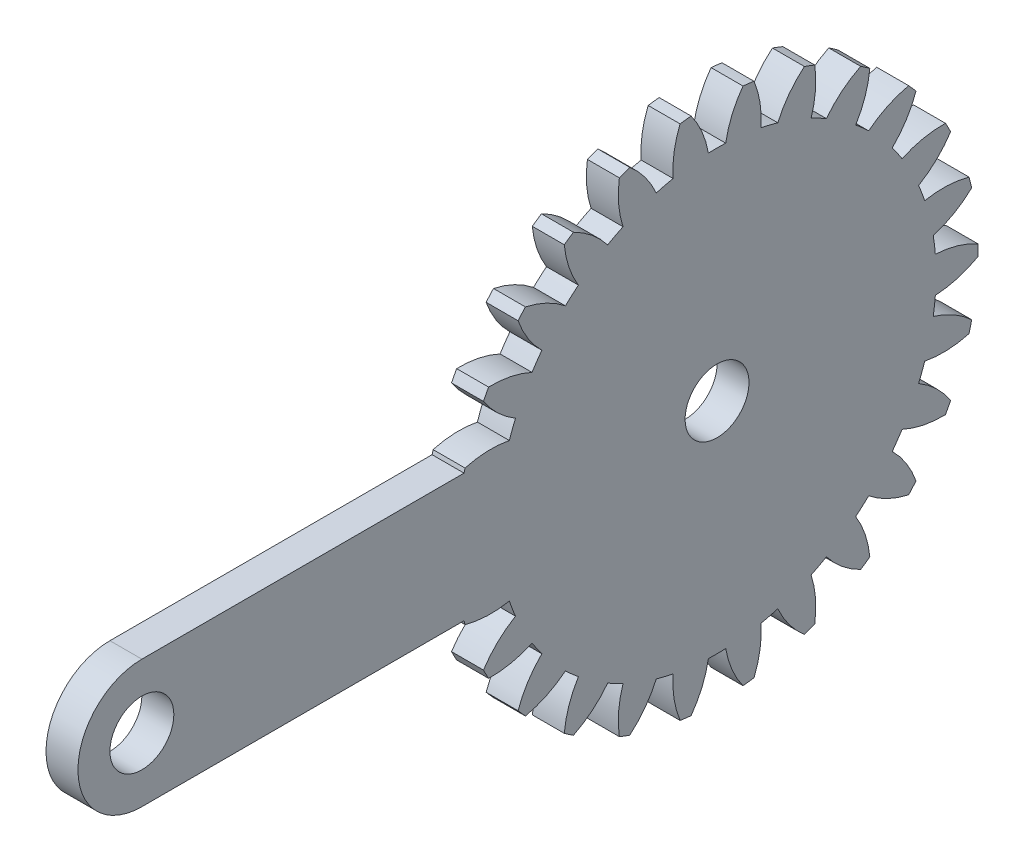
SolidWorks part; units mm, degrees
ref_plane "Plane1" through (0, 0, 0) normal (0, 0, 1) x (1, 0, 0)
ref_plane "Plane2" through (0, 0, 0) normal (0, 1, 0) x (1, 0, 0)
ref_plane "Plane3" through (0, 0, 0) normal (1, 0, 0) x (0, 0, -1)
sketch "HoldingSke" plane through (0, 0, 0) normal (0, 1, 0) x (1, 0, 0)
  line L0 (0, 0) -> (0.5136, -0.2505)
  line L1 (-15, 0) -> (100, 0) construction
  line L2 (0, 0) -> (-2.1039, 2.3779)
  line L3 (0, 0) -> (-11.863, 4.5341)
  line L4 (0, 0) -> (7.762, 3.7858)
  line L5 (0, 0) -> (-46.8476, -17.4728)
  line L6 (0, 0) -> (-2.4869, -1.6779)
  line L7 (-2.1039, 2.3779) -> (8.6586, 51.2059)
  line L8 (-76.2, 54.61) -> (-75.2, 54.61)
  line L9 (-71.009, 38.7566) -> (-53.1078, 45.2721)
  line L10 (-76.2, 71.12) -> (104.1128, 71.12)
  line L11 (0, 0) -> (-3, 0)
  line L12 (-76.2, 101.6) -> (-76.147, 101.6)
  line L13 (24.9733, 27.94) -> (52.9518, 28.4284)
  line L14 (24.9733, 27.94) -> (24.9743, 27.94)
  line L15 (24.9733, 27.94) -> (100.4006, 29.5858)
  line L16 (-63.627, -1.75) -> (-12.827, -1.75)
  circle A0 centre (0, 0) radius 3
  circle A1 centre (0, 0) radius 20.5615
  circle A2 centre (0, 0) radius 37.5
  circle A3 centre (0, 0) radius 3
  dimension "MHD" = 41.123
  dimension "Hub_dia" = 75
  dimension "Bore" = 6
  dimension "MBD" = 6
  dimension "Num_teeth" = 26
  dimension "Pitch" = 0.5714
  dimension "Overall_len" = 50
  dimension "Show_teeth" = 26
  dimension "Thickness" = 3
  dimension "OAL" = 50.0001
  dimension "T_dim" = 1
  dimension "Ap" = 20
  dimension "H" = 19.05
  dimension "Pitch_radius" = 180.3128
  dimension "Width" = 3
  dimension "Backlash" = 0.053
  dimension "Addendum_fac" = 1
  dimension "Dedendum_fac" = 1.25
  dimension "Clearance_fac" = 0.25
  dimension "Dedendum_add" = 0.001
  dimension "Module" = 1.75
sketch "BasProSke" plane through (0, 0, 0) normal (0, 1, 0) x (1, 0, 0)
  line L0 (-10, 0) -> (60, 0) construction
  line L1 (0, 0) -> (0, 24.5)
  line L2 (0, 0) -> (3, 0)
  line L3 (3, 0) -> (3, 24.5)
  line L4 (3, 24.5) -> (0, 24.5)
  dimension "Thickness" = 3
  dimension "Diameter" = 49
revolve "Base-Revolve" add sketch "BasProSke" angle 360 about L0
sketch "TooCutSke" plane through (0, 0, 0) normal (1, 0, 0) x (0, 0, -1)
  line L1 (0, 0) -> (0, 107) construction
  line L2 (0, 0) -> (-1.4663, 22.7027) construction
  line L3 (0, 0) -> (-5.4757, 45.0966) construction
  line L4 (-1.4663, 22.7027) -> (-2.7379, 22.5483) construction
  arc A0 (0.8134, 20.5454) -> (-0.8134, 20.5454) centre (0, 0) ccw
  arc A1 (2.4537, 24.4024) -> (-2.4537, 24.4024) centre (0, 0) ccw
  circle A2 centre (0, 0) radius 22.75 construction
  circle A3 centre (0, 0) radius 21.378 construction
  arc A4 (-0.8134, 20.5454) -> (-2.4537, 24.4024) centre (-9.7827, 19.0084) ccw
  arc A5 (2.4537, 24.4024) -> (0.8134, 20.5454) centre (9.7827, 19.0084) ccw
  dimension "Root_dia" = 41.123
  dimension "Overcut_dia" = 49.0508
  dimension "Pitch_dia" = 45.5
  dimension "Base_dia" = 42.756
  dimension "Flank_rad" = 9.1
  dimension "Half_ang" = 6.923
  dimension "Half_CT" = 1.2809
extrude "ToothCut" cut sketch "TooCutSke" along normal through all
fillet "Breaks" [suppressed] radius 0.035
fillet "RootFillets" [suppressed] radius 0.4385
pattern_circular "TeethCuts" count 26 every 13.846 about axis through (-10, 0, 0) along (1, 0, 0) of "ToothCut", "RootFillets", "Breaks"
sketch "HubNeaOneSke" plane through (0, 0, 0) normal (-1, 0, 0) x (0, 0, 1)
  circle A0 centre (0, 0) radius 20.5615
  dimension "Diameter" = 41.123
extrude "HubNearOne" [suppressed] add sketch "HubNeaOneSke" along normal blind 47.0001
sketch "HubNeaBotSke" plane through (0, 0, 0) normal (-1, 0, 0) x (0, 0, 1)
  circle A0 centre (0, 0) radius 20.5615
  dimension "Diameter" = 41.123
extrude "HubNearBoth" [suppressed] add sketch "HubNeaBotSke" along normal blind 23.5
ref_plane "FarPln" through (3, 0, 0) normal (1, 0, 0) x (0, 0, -1)
sketch "HubFarSke" plane through (3, 0, 0) normal (1, 0, 0) x (0, 0, -1)
  circle A0 centre (0, 0) radius 20.5615
  dimension "Diameter" = 41.123
extrude "HubFar" [suppressed] add sketch "HubFarSke" along normal blind 23.5
sketch "BorSke" plane through (0, 0, 0) normal (1, 0, 0) x (0, 0, -1)
  circle A0 centre (0, 0) radius 3
  dimension "Diameter" = 6
extrude "Bore" cut sketch "BorSke" along normal mid plane 100.0001
sketch "KeySke" plane through (0, 0, 0) normal (1, 0, 0) x (0, 0, -1)
  line L0 (-1, 0) -> (-1, 4)
  line L1 (-1, 4) -> (1, 4)
  line L2 (1, 4) -> (1, 0)
  line L3 (0, 0) -> (0, 34) construction
  line L4 (-1, 0) -> (1, 0)
  dimension "Offset" = 4
  dimension "Width" = 2
extrude "Keyway" [suppressed] cut sketch "KeySke" along normal mid plane 100.0001
pattern_circular "Keyway2" [suppressed] count 2 every 90 about axis through (-10, 0, 0) along (1, 0, 0)
sketch "Sketch2" plane through (0, 0, 0) normal (1, 0, 0) x (0, 0, -1)
  line L0 (0, 0) -> (-54, 0) construction
  line L1 (0, -6) -> (-54, -6)
  line L2 (0, 6) -> (-54, 6)
  arc A0 (0, -6) -> (0, 6) centre (0, 0) ccw
  arc A1 (-54, 6) -> (-54, -6) centre (-54, 0) ccw
  circle A2 centre (-54, 0) radius 3
  circle A3 centre (0, 0) radius 3
  point P3 (-27, 0)
  dimension "D1" = 54
  dimension "D2" = 12
extrude "Boss-Extrude1" add sketch "Sketch2" along normal blind 3
equation "' \"Module@HoldingSke\" = 6.35"
equation "' \"Num_teeth@HoldingSke\" = 12"
equation "' \"Ap@HoldingSke\" =  20"
equation "' \"Ap@HoldingSke\" = 20"
equation "' \"Width@HoldingSke\" = 0.5 * 25.4"
equation "' \"Hub_dia@HoldingSke\"= 1 * 25.4"
equation "' \"Hub_dia@HoldingSke\" = 1 * 25.4"
equation "' \"Overall_len@HoldingSke\" = 1.0 * 25.4"
equation "' \"Bore@HoldingSke\" = 0.75 * 25.4"
equation "' \"T_dim@HoldingSke\" = 0.1 * 25.4"
equation "' \"Width@KeySke\" = 0.25 * 25.4"
equation "' \"Show_teeth@HoldingSke\" = 13"
equation "' \"Backlash@HoldingSke\" = 0.009 * 25.4"
equation "' \"Addendum_fac@HoldingSke\" = 1.0"
equation "' \"Dedendum_fac@HoldingSke\" = 1.25"
equation "' \"Dedendum_add@HoldingSke\" = 0.00005 * 25.4"
equation "' \"Clearance_fac@HoldingSke\" = 0.25"
equation "\"Pitch@HoldingSke\" = 1 / \"Module@HoldingSke\""
equation "\"Overcut_dia@TooCutSke\" = (\"Num_teeth@HoldingSke\" + 2 * \"Addendum_fac@HoldingSke\") / \"Pitch@HoldingSke\" + 0.002 * 25.4"
equation "\"Pitch_dia@TooCutSke\" = \"Num_teeth@HoldingSke\" / \"Pitch@HoldingSke\""
equation "\"Base_dia@TooCutSke\" = \"Num_teeth@HoldingSke\" / \"Pitch@HoldingSke\" * cos((\"Ap@HoldingSke\"  * 3.14159265 / 180))"
equation "\"Root_dia@TooCutSke\" = (\"Num_teeth@HoldingSke\" + 2) / \"Pitch@HoldingSke\" - 2 * (\"Addendum_fac@HoldingSke\" + \"Dedendum_fac@HoldingSke\") / \"Pitch@HoldingSke\" - \"Dedendum_add@HoldingSke\" * 2"
equation "\"Half_ang@TooCutSke\" = 180 / \"Num_teeth@HoldingSke\""
equation "\"Half_CT@TooCutSke\" = \"Num_teeth@HoldingSke\" / \"Pitch@HoldingSke\" * sin((3.14159265 / 2 / \"Num_teeth@HoldingSke\")) / 2 - 7 * \"Backlash@HoldingSke\" / 4"
equation "\"Flank_rad@TooCutSke\" = \"Num_teeth@HoldingSke\" / \"Pitch@HoldingSke\" / 5"
equation "\"Radius@RootFillets\" = \"Clearance_fac@HoldingSke\" / \"Pitch@HoldingSke\" + \"Dedendum_add@HoldingSke\""
equation "\"Break_rad@Breaks\" = 0.02 / \"Pitch@HoldingSke\""
equation "\"Thickness@HoldingSke\" = \"Width@HoldingSke\""
equation "\"OAL@HoldingSke\" = \"Thickness@HoldingSke\""
equation "\"MHD@HoldingSke\" = (\"Num_teeth@HoldingSke\" + 2) / \"Pitch@HoldingSke\" - 2 * (\"Addendum_fac@HoldingSke\" + \"Dedendum_fac@HoldingSke\")  / \"Pitch@HoldingSke\" - \"Dedendum_add@HoldingSke\" * 2"
equation "\"MBD@HoldingSke\" = (\"Num_teeth@HoldingSke\" + 2) / \"Pitch@HoldingSke\" - 2 * (\"Addendum_fac@HoldingSke\" + \"Dedendum_fac@HoldingSke\")  / \"Pitch@HoldingSke\" - \"Dedendum_add@HoldingSke\" * 2 - 0.002 * 25.4"
equation "\"MHD@HoldingSke\" = ((sgn( \"MHD@HoldingSke\" - \"Hub_dia@HoldingSke\" )-1)*( \"MHD@HoldingSke\" - \"Hub_dia@HoldingSke\" ))/-2+ \"Hub_dia@HoldingSke\""
equation "\"MBD@HoldingSke\" = ((sgn( \"MBD@HoldingSke\" - \"Bore@HoldingSke\" )-1)*( \"MBD@HoldingSke\" - \"Bore@HoldingSke\" ))/-2+ \"Bore@HoldingSke\""
equation "\"OAL@HoldingSke\" = ((sgn( \"OAL@HoldingSke\" - \"Overall_len@HoldingSke\" )+1)*( \"OAL@HoldingSke\" - \"Overall_len@HoldingSke\" ))/2 + \"Overall_len@HoldingSke\" + 0.000002 * 25.4"
equation "\"Num_teeth@TeethCuts\" = int( \"Show_teeth@HoldingSke\" ) + 1"
equation "\"Num_teeth@TeethCuts\" = ((sgn( \"Num_teeth@TeethCuts\" - \"Num_teeth@HoldingSke\" )-1)*( \"Num_teeth@TeethCuts\" - \"Num_teeth@HoldingSke\" ))/-2+ \"Num_teeth@HoldingSke\""
equation "\"Num_teeth@TeethCuts\" = ((sgn( \"Num_teeth@TeethCuts\" - 2.0)+1)*( \"Num_teeth@TeethCuts\" - 2.0))/2 +2.0"
equation "\"Angle@TeethCuts\" = 360.0 / \"Num_teeth@HoldingSke\""
equation "\"Diameter@BasProSke\" = (\"Num_teeth@HoldingSke\" + 2 * \"Addendum_fac@HoldingSke\") / \"Pitch@HoldingSke\""
equation "\"Thickness@BasProSke\"  = \"Thickness@HoldingSke\""
equation "' \"Fillet_rad@BasProSke\" =  \"Thickness@HoldingSke\" * 0.05"
equation "' \"Fillet_rad@BasProSke\" = \"Thickness@HoldingSke\" * 0.05"
equation "\"MHD@HoldingSke\" = ((sgn( \"MHD@HoldingSke\" - \"Root_dia@TooCutSke\" )-1)*( \"MHD@HoldingSke\" - \"Root_dia@TooCutSke\" ))/-2+ \"Root_dia@TooCutSke\""
equation "\"Diameter@HubNeaOneSke\" = \"MHD@HoldingSke\""
equation "\"Length@HubNearOne\" = \"OAL@HoldingSke\" - \"Thickness@BasProSke\""
equation "\"Diameter@HubNeaBotSke\" = \"MHD@HoldingSke\""
equation "\"Length@HubNearBoth\" = ( \"OAL@HoldingSke\" - \"Thickness@BasProSke\" ) / 2.0"
equation "\"Thickness@FarPln\" = \"Thickness@BasProSke\""
equation "\"Diameter@HubFarSke\" = \"MHD@HoldingSke\""
equation "\"Length@HubFar\" = ( \"OAL@HoldingSke\" - \"Thickness@BasProSke\" ) / 2.0"
equation "\"Diameter@BorSke\" = \"MBD@HoldingSke\""
equation "\"D1@Bore\" = \"OAL@HoldingSke\" * 2.0"
equation "\"D1@Keyway\" = \"OAL@HoldingSke\" * 2.0"
equation "\"Offset@KeySke\" = \"T_dim@HoldingSke\" + \"MBD@HoldingSke\" / 2.0"
